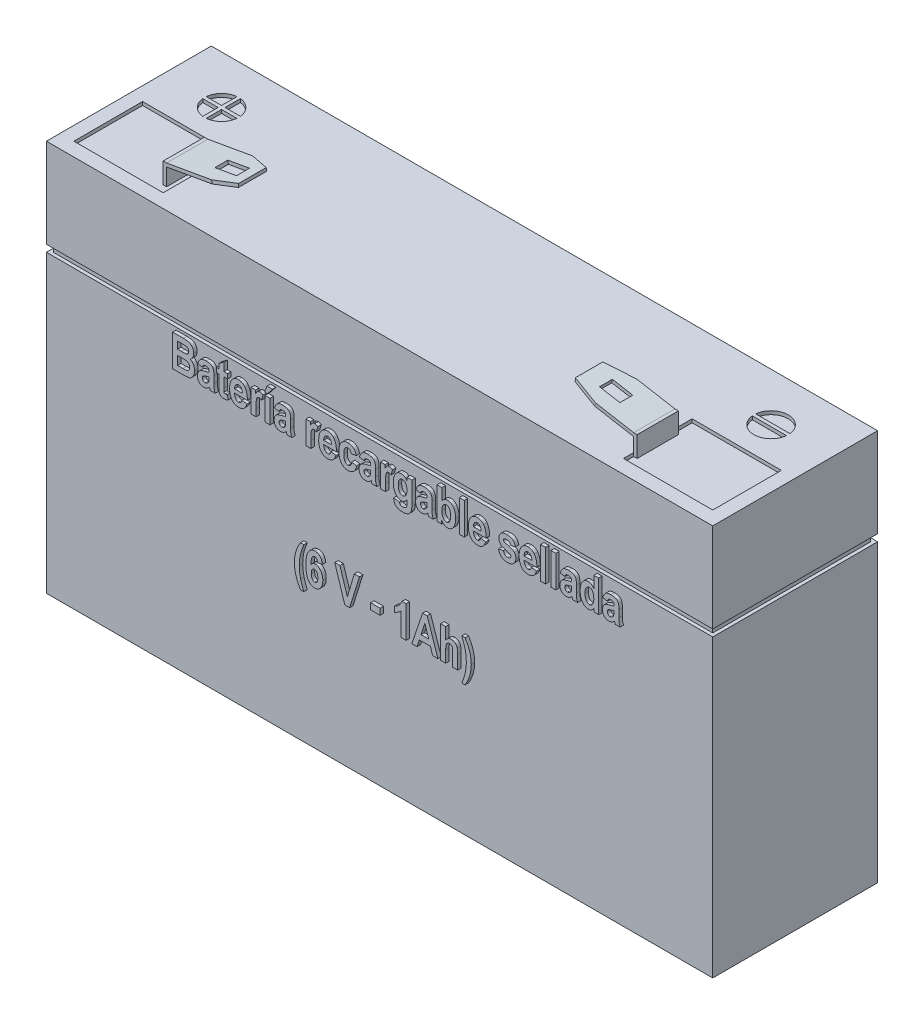
SolidWorks part; units mm, degrees
other "Marca1"
sketch "Croquis9" plane through (-48.5, 33.1751, 12) normal (-0.9538, 0.2719, 0.1281) x (0.2899, 0.9446, 0.1539)
ref_plane "Alzado" through (0, 0, 0) normal (0, 0, 1) x (1, 0, 0)
ref_plane "Planta" through (0, 0, 0) normal (0, 1, 0) x (1, 0, 0)
ref_plane "Vista lateral" through (0, 0, 0) normal (1, 0, 0) x (0, 0, -1)
sketch "Croquis1" plane through (0, 0, 0) normal (0, 0, 1) x (1, 0, 0)
  line L1 (-48.5, -28.5) -> (48.5, -28.5)
  line L2 (-48.5, -28.5) -> (-48.5, 28.5)
  line L3 (-48.5, 28.5) -> (48.5, 28.5)
  line L4 (48.5, -28.5) -> (48.5, 28.5)
  line L5 (-48.5, -28.5) -> (48.5, 28.5) construction
  line L6 (-48.5, 28.5) -> (48.5, -28.5) construction
  point P0 (0, 0)
  dimension "D1" = 97
  dimension "D2" = 57
extrude "Saliente-Extruir1" add sketch "Croquis1" along normal mid plane 24
sketch "Croquis2" plane through (48.5, 0, 0) normal (1, 0, 0) x (0, 0, -1)
  line L0 (-12, 15) -> (12, 15) construction
  line L1 (-12, -28.5) -> (-12, 28.5) construction
  line L2 (12, -28.5) -> (12, 28.5) construction
  line L3 (-12, 28.5) -> (12, 28.5) construction
  line L5 (-11.5, 14.5) -> (-12.5, 14.5)
  line L6 (-11.5, 14.5) -> (-11.5, 15.5)
  line L7 (-11.5, 15.5) -> (-12.5, 15.5)
  line L8 (-12.5, 14.5) -> (-12.5, 15.5)
  line L9 (-11.5, 14.5) -> (-12.5, 15.5) construction
  line L10 (-11.5, 15.5) -> (-12.5, 14.5) construction
  dimension "D1" = 13.5
  dimension "D2" = 1
  dimension "D3" = 1
extrude "Cortar-Extruir1" cut sketch "Croquis2" against normal up to next
ref_plane "Plano1" through (0, 0, 0) normal (0, 0, 1) x (1, 0, 0)
mirror "Simetría2" about plane through (0, 0, 0) normal (0, 0, 1) of "Cortar-Extruir1"
ref_plane "Plano2" through (0, 0, 0) normal (1, 0, 0) x (0, 0, -1)
sketch "Croquis4" plane through (0, 0, 12) normal (0, 0, 1) x (1, 0, 0)
  line L0 (48.5, 14.5) -> (48.5, 15.5) construction
  line L1 (48, 14.5) -> (49, 14.5)
  line L2 (48, 14.5) -> (48, 15.5)
  line L3 (48, 15.5) -> (49, 15.5)
  line L4 (49, 14.5) -> (49, 15.5)
  line L5 (48, 14.5) -> (49, 15.5) construction
  line L6 (48, 15.5) -> (49, 14.5) construction
  point P0 (48.5, 15)
  dimension "D1" = 1
  dimension "D2" = 1
extrude "Cortar-Extruir2" cut sketch "Croquis4" against normal up to next
mirror "Simetría3" about plane through (0, 0, 0) normal (1, 0, 0) of "Cortar-Extruir2"
sketch "Croquis5" plane through (0, 28.5, 0) normal (0, 1, 0) x (1, 0, 0)
  line L0 (-48.5, -12) -> (-48.5, 12) construction
  line L2 (-46.5, -10) -> (46.5, -10) construction
  line L4 (-46.5, -10) -> (-46.5, 10) construction
  line L5 (-46.5, 10) -> (46.5, 10) construction
  line L6 (46.5, -10) -> (46.5, 10) construction
  line L7 (-46.5, -10) -> (46.5, 10) construction
  line L8 (-46.5, 10) -> (46.5, -10) construction
  line L10 (48.5, 12) -> (-48.5, 12) construction
  line L11 (-52.0538, 0) -> (55.1173, 0) construction
  line L12 (-46.5, 10) -> (-33.5, 10)
  line L13 (-46.5, 10) -> (-46.5, -10)
  line L14 (-46.5, -10) -> (-33.5, -10)
  line L15 (-33.5, 10) -> (-33.5, -10)
  line L16 (46.5, 10) -> (33.5, 10)
  line L17 (46.5, 10) -> (46.5, -10)
  line L18 (46.5, -10) -> (33.5, -10)
  line L19 (33.5, 10) -> (33.5, -10)
  line L20 (-33.5, 0) -> (-46.5, 10) construction
  line L21 (33.5, 0) -> (46.5, 10) construction
  line L22 (-46.5, 0) -> (-33.5, 0)
  line L23 (-42.4875, 4.75) -> (-37.5125, 4.75)
  line L25 (-42.4875, 5.25) -> (-37.5125, 5.25)
  line L27 (-42.4914, 4.7925) -> (-37.5086, 5.2075) construction
  line L28 (-42.4914, 5.2075) -> (-37.5086, 4.7925) construction
  line L30 (-40.25, 2.5125) -> (-40.25, 7.4875)
  line L32 (-39.75, 2.5125) -> (-39.75, 7.4875)
  line L33 (-40.2077, 2.5086) -> (-39.7923, 7.4914) construction
  line L34 (-40.2077, 7.4914) -> (-39.7923, 2.5086) construction
  line L35 (37.5125, 4.75) -> (42.4875, 4.75)
  line L37 (37.5125, 5.25) -> (42.4875, 5.25)
  line L39 (37.5106, 4.7698) -> (42.4894, 5.2302) construction
  line L40 (37.5106, 5.2302) -> (42.4894, 4.7698) construction
  line L41 (33.5, 0) -> (46.5, 0)
  circle A0 centre (-40, 5) radius 2.5
  circle A1 centre (40, 5) radius 2.5
  point P0 (0, 0)
  dimension "D5" = 5
  dimension "D6" = 5
  dimension "D1" = 2
  dimension "D2" = 2
  dimension "D3" = 13
  dimension "D4" = 13
  dimension "D7" = 0.5
extrude "Cortar-Extruir3" cut sketch "Croquis5" against normal blind 0.5 contours L22 L13 L14 L15 | L41 L19 L18 L17 | L35 A1 | L37 A1 | L30 A0 L25 | L25 A0 L32 | L23 A0 L30 | L32 A0 L23
ref_plane "Plano3" through (0, 0, 9) normal (0, 0, 1) x (1, 0, 0)
sketch "Croquis6" plane through (0, 0, 9) normal (0, 0, 1) x (1, 0, 0)
  line L0 (-34.5, 28.5) -> (-34.5, 52.0771) construction
  line L1 (48.5, 28.5) -> (-48.5, 28.5) construction
  line L2 (-48.5, 28.5) -> (-48.5, 15.5) construction
  line L3 (0, -28.5) -> (0, 84.6398) construction
  line L5 (-34, 31) -> (-24.5, 32.6751)
  line L6 (-34.5, 28.5) -> (-34, 28.5)
  line L7 (-34.5, 28.5) -> (-34.5, 31.5)
  line L8 (-34.5, 31.5) -> (-34, 31.5)
  line L9 (-34, 28.5) -> (-34, 31)
  line L10 (-34, 31.5) -> (-24.5, 33.1751)
  line L11 (-24.5, 33.1751) -> (-24.5, 32.6751)
  line L12 (-48.5, -28.5) -> (48.5, -28.5) construction
  line L13 (34.5, 28.5) -> (34, 28.5)
  line L14 (34, 28.5) -> (34, 31)
  line L15 (34.5, 28.5) -> (34.5, 31.5)
  line L16 (34.5, 31.5) -> (34, 31.5)
  line L17 (24.5, 33.1751) -> (24.5, 32.6751)
  line L18 (34, 31) -> (24.5, 32.6751)
  line L19 (34, 31.5) -> (24.5, 33.1751)
  dimension "D1" = 14
  dimension "D3" = 3
  dimension "D4" = 0.5
  dimension "D5" = 0.5
  dimension "D6" = 80
  dimension "D7" = 10
  dimension "D8" = 0.5
extrude "Saliente-Extruir2" add sketch "Croquis6" against normal blind 6 separate body
sketch "Croquis7" plane through (-6.412, 36.3645, 0) normal (-0.1736, 0.9848, 0) x (0.9848, 0.1736, 0)
  line L0 (-21.367, 0.8123) -> (-21.367, -10.9274) construction
  line L1 (-18.367, -3) -> (-18.367, -9) construction
  line L2 (-18.367, -6) -> (-25.951, -6) construction
  line L3 (-21.367, -9) -> (-18.367, -8)
  line L4 (-22.9689, -6.9425) -> (-19.765, -6.9425)
  line L5 (-22.9689, -6.9425) -> (-22.9689, -5.0575)
  line L6 (-22.9689, -5.0575) -> (-19.765, -5.0575)
  line L7 (-19.765, -6.9425) -> (-19.765, -5.0575)
  line L8 (-22.9689, -6.9425) -> (-19.765, -5.0575) construction
  line L9 (-22.9689, -5.0575) -> (-19.765, -6.9425) construction
  line L10 (-18.367, -9) -> (-28.0135, -9) construction
  line L11 (-21.367, -3) -> (-18.367, -4)
  line L12 (-18.367, -3) -> (-28.0135, -3) construction
  line L13 (-21.367, -9) -> (-18.367, -9)
  line L14 (-18.367, -9) -> (-18.367, -8)
  line L15 (-18.367, -4) -> (-18.367, -3)
  line L16 (-18.367, -3) -> (-21.367, -3)
  line L17 (0, 23.3324) -> (0, -23.3287) construction
  point P6 (-21.367, -6)
  dimension "D1" = 3
  dimension "D2" = 2
  dimension "D3" = 2
extrude "Cortar-Extruir4" cut sketch "Croquis7" against normal up to next (0.4924 mm away) contours L5 L4 L7 L6 | L14 L3 L13 | L16 L11 L15
sketch "Croquis8" plane through (6.412, 36.3645, 0) normal (0.1736, 0.9848, 0) x (0.9848, -0.1736, 0)
  line L0 (22.367, 1.7713) -> (22.367, -19.7713) construction
  line L1 (18.367, -3) -> (18.367, -9) construction
  line L2 (18.367, -6) -> (26.9491, -6) construction
  line L3 (18.367, -8) -> (22.367, -9)
  line L4 (23.8705, -6.9369) -> (20.8635, -6.9369)
  line L5 (23.8705, -6.9369) -> (23.8705, -5.0631)
  line L6 (23.8705, -5.0631) -> (20.8635, -5.0631)
  line L7 (20.8635, -6.9369) -> (20.8635, -5.0631)
  line L8 (23.8705, -6.9369) -> (20.8635, -5.0631) construction
  line L9 (23.8705, -5.0631) -> (20.8635, -6.9369) construction
  line L10 (18.367, -4) -> (22.367, -3)
  line L11 (18.367, -4) -> (18.367, -3)
  line L12 (18.367, -3) -> (22.367, -3)
  line L13 (18.367, -8) -> (18.367, -9)
  line L14 (28.0135, -9) -> (18.367, -9) construction
  line L15 (18.367, -9) -> (22.367, -9)
  line L16 (28.0135, -3) -> (18.367, -3) construction
  point P6 (22.367, -6)
  dimension "D1" = 4
  dimension "D2" = 2
  dimension "D3" = 2
extrude "Cortar-Extruir5" cut sketch "Croquis8" against normal up to next (0.4924 mm away)
sketch "Croquis10" plane through (0, 0, 12) normal (0, 0, 1) x (1, 0, 0)
  line L0 (-49.0892, 9.5) -> (50.9108, 9.5) construction
  line L1 (-48, 14.5) -> (48, 14.5) construction
  text T0 "<b>Batería recargable sellada</b>\r\n\r\n<b>(6 V - 1Ah)</b>" font "Arial Narrow" height in points 18
  dimension "D1" = 100
  dimension "D2" = 50
  dimension "D3" = 5
extrude "Saliente-Extruir4" add sketch "Croquis10" along normal blind 0.5
